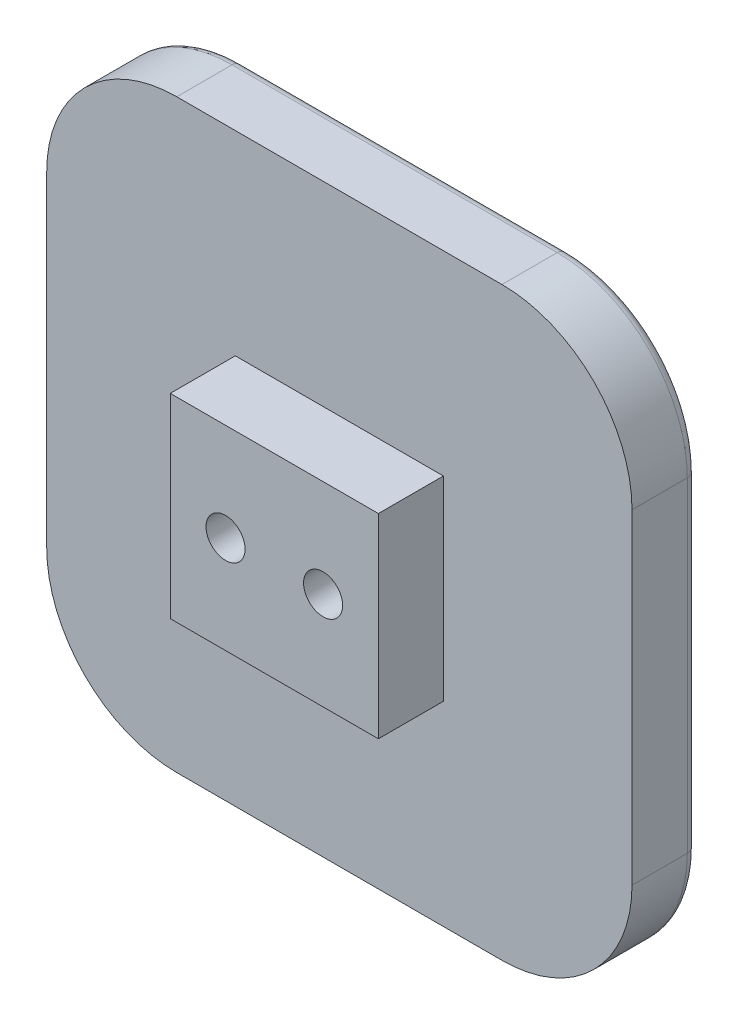
SolidWorks part; units mm, degrees
ref_plane "Ön Düzlem" through (0, 0, 0) normal (0, 0, 1) x (1, 0, 0)
ref_plane "Üst Düzlem" through (0, 0, 0) normal (0, 1, 0) x (1, 0, 0)
ref_plane "Sağ Düzlem" through (0, 0, 0) normal (1, 0, 0) x (0, 0, -1)
sketch "Çizim1" plane through (0, 0, 0) normal (0, 0, 1) x (1, 0, 0)
  line L0 (-41.5414, -1.1109) -> (-41.5414, 48.8891)
  line L1 (-21.5414, 68.8891) -> (28.4586, 68.8891)
  line L2 (-21.5414, -21.1109) -> (28.4586, -21.1109)
  line L3 (48.4586, -1.1109) -> (48.4586, 48.8891)
  arc A0 (-21.5414, 68.8891) -> (-41.5414, 48.8891) centre (-21.5414, 48.8891) ccw
  arc A1 (28.4586, 68.8891) -> (48.4586, 48.8891) centre (28.4586, 48.8891) cw
  arc A2 (28.4586, -21.1109) -> (48.4586, -1.1109) centre (28.4586, -1.1109) ccw
  arc A3 (-21.5414, -21.1109) -> (-41.5414, -1.1109) centre (-21.5414, -1.1109) cw
extrude "Yükseklik-Ekstrüzyon1" add sketch "Çizim1" along normal blind 20
sketch "Sketch1" plane through (0, 0, 0) normal (0, 0, 1) x (1, 0, 0)
  circle A0 centre (-4.0414, 23.8891) radius 2.5
  circle A1 centre (10.9586, 23.8891) radius 2.5
extrude "Cut-Extrude1" cut sketch "Sketch1" along normal blind 44 and the other way blind 10
sketch "Sketch2" plane through (0, 0, 0) normal (0, 0, 1) x (1, 0, 0)
  line L0 (-12.5414, 38.8891) -> (19.4586, 38.8891)
  line L3 (19.4586, 38.8891) -> (19.4586, 68.8891)
  line L4 (28.4586, 68.8891) -> (-21.5414, 68.8891) construction
  line L5 (19.4586, 68.8891) -> (-12.5414, 68.8891)
  line L6 (-12.5414, 68.8891) -> (-12.5414, 38.8891)
extrude "Cut-Extrude3" cut sketch "Sketch2" along normal blind 27
sketch "Sketch3" plane through (0, 0, 0) normal (0, 0, 1) x (1, 0, 0)
  line L1 (-12.5414, 38.8891) -> (19.4586, 38.8891)
  line L2 (-12.5414, 38.8891) -> (-12.5414, 68.8891)
  line L3 (-12.5414, 68.8891) -> (19.4586, 68.8891)
  line L4 (19.4586, 38.8891) -> (19.4586, 68.8891)
extrude "Boss-Extrude1" add sketch "Sketch3" along normal blind 16
sketch "Sketch4" plane through (0, 0, 0) normal (0, 0, 1) x (1, 0, 0)
  line L1 (15.6929, 23.8891) -> (13.3258, 27.9891)
  line L2 (13.3258, 27.9891) -> (8.5915, 27.9891)
  line L3 (8.5915, 27.9891) -> (6.2244, 23.8891)
  line L4 (6.2244, 23.8891) -> (8.5915, 19.7891)
  line L5 (8.5915, 19.7891) -> (13.3258, 19.7891)
  line L6 (13.3258, 19.7891) -> (15.6929, 23.8891)
  line L7 (0.6929, 23.8891) -> (-1.6742, 27.9891)
  line L8 (-1.6742, 27.9891) -> (-6.4085, 27.9891)
  line L9 (-6.4085, 27.9891) -> (-8.7756, 23.8891)
  line L10 (-8.7756, 23.8891) -> (-6.4085, 19.7891)
  line L11 (-6.4085, 19.7891) -> (-1.6742, 19.7891)
  line L12 (-1.6742, 19.7891) -> (0.6929, 23.8891)
  circle A0 centre (10.9586, 23.8891) radius 4.1 construction
  circle A2 centre (-4.0414, 23.8891) radius 4.1 construction
extrude "Cut-Extrude4" cut sketch "Sketch4" along normal blind 4
sketch "Sketch5" plane through (0, 0, 0) normal (0, 0, 1) x (1, 0, 0)
  line L1 (18.9616, 32.8218) -> (-14.5543, 32.8218)
  line L2 (18.9616, 32.8218) -> (18.9616, 14.5135)
  line L3 (18.9616, 14.5135) -> (-14.5543, 14.5135)
  line L4 (-14.5543, 32.8218) -> (-14.5543, 14.5135)
extrude "Boss-Extrude2" add sketch "Sketch5" along normal blind 10
sketch "Sketch6" plane through (0, 0, 0) normal (0, 0, 1) x (1, 0, 0)
  circle A0 centre (-4.0414, 23.8891) radius 2.5
  circle A1 centre (10.9586, 23.8891) radius 2.5
extrude "Cut-Extrude5" cut sketch "Sketch6" against normal blind 25 and the other way blind 53
sketch "Sketch7" plane through (0, 0, 0) normal (0, 0, 1) x (1, 0, 0)
  line L2 (-12.5414, 68.8891) -> (-49.0364, 68.8891)
  line L3 (-12.5414, 68.8891) -> (-12.5414, -22.5963)
  line L4 (-12.5414, -22.5963) -> (-49.0364, -22.5963)
  line L5 (-49.0364, 68.8891) -> (-49.0364, -22.5963)
  line L6 (19.4586, 68.8891) -> (57.7649, 68.8891)
  line L7 (19.4586, 68.8891) -> (19.4586, -22.5963)
  line L8 (19.4586, -22.5963) -> (57.7649, -22.5963)
  line L9 (57.7649, 68.8891) -> (57.7649, -22.5963)
extrude "Cut-Extrude7" cut sketch "Sketch7" along normal blind 30
sketch "Sketch8" plane through (0, 0, 0) normal (0, 0, 1) x (1, 0, 0)
  line L0 (-41.5414, 68.8891) -> (-12.5414, 68.8891)
  line L1 (19.4586, 68.8891) -> (48.4586, 68.8891)
  line L3 (-41.5414, 68.8891) -> (-41.5414, -21.1109)
  line L4 (-41.5414, -21.1109) -> (-12.5414, -21.1109)
  line L5 (-12.5414, 68.8891) -> (-12.5414, -21.1109)
  line L8 (48.4586, 68.8891) -> (48.4586, -21.1109)
  line L9 (48.4586, -21.1109) -> (19.4586, -21.1109)
  line L10 (19.4586, 68.8891) -> (19.4586, -21.1109)
extrude "Boss-Extrude3" add sketch "Sketch8" along normal blind 10
sketch "Sketch9" plane through (0, 0, 0) normal (0, 0, 1) x (1, 0, 0)
  line L0 (-41.5414, 68.8891) -> (-21.5414, 68.8891)
  line L1 (-12.5414, 68.8891) -> (-41.5414, 68.8891) construction
  line L3 (-41.5414, 68.8891) -> (-41.5414, 48.8891)
  line L9 (48.4586, 68.8891) -> (48.4586, 48.8891)
  line L10 (48.4586, 68.8891) -> (28.4586, 68.8891)
  line L11 (48.4586, -21.1109) -> (28.4586, -21.1109)
  line L12 (48.4586, -21.1109) -> (48.4586, -1.1109)
  line L13 (-41.5414, -21.1109) -> (-41.5414, -1.1109)
  line L14 (-41.5414, -21.1109) -> (-21.5414, -21.1109)
  arc A0 (-21.5414, 68.8891) -> (-41.5414, 48.8891) centre (-21.5414, 48.8891) ccw
  arc A1 (28.4586, 68.8891) -> (48.4586, 48.8891) centre (28.4586, 48.8891) cw
  arc A2 (28.4586, -21.1109) -> (48.4586, -1.1109) centre (28.4586, -1.1109) ccw
  arc A3 (-21.5414, -21.1109) -> (-41.5414, -1.1109) centre (-21.5414, -1.1109) cw
extrude "Cut-Extrude8" cut sketch "Sketch9" along normal blind 10
sketch "Sketch10" plane through (0, 0, 0) normal (0, 0, 1) x (1, 0, 0)
  line L0 (19.4586, 38.8891) -> (19.4586, -21.1109) construction
  line L1 (-12.5414, 68.8891) -> (19.4586, 68.8891)
  line L2 (-12.5414, 68.8891) -> (-12.5414, 38.8891)
  line L3 (-12.5414, 38.8891) -> (19.4586, 38.8891)
  line L4 (19.4586, 68.8891) -> (19.4586, 38.8891)
  line L5 (-12.5414, -21.1109) -> (19.4586, -21.1109)
  line L6 (-12.5414, -21.1109) -> (-12.5414, 8.8891)
  line L7 (-12.5414, 8.8891) -> (19.4586, 8.8891)
  line L8 (19.4586, -21.1109) -> (19.4586, 8.8891)
extrude "Cut-Extrude9" cut sketch "Sketch10" along normal blind 28
sketch "Sketch11" plane through (0, 0, 0) normal (0, 0, 1) x (1, 0, 0)
  line L1 (-12.5414, 38.8891) -> (19.4586, 38.8891)
  line L2 (-12.5414, 38.8891) -> (-12.5414, 68.8891)
  line L3 (-12.5414, 68.8891) -> (19.4586, 68.8891)
  line L4 (19.4586, 38.8891) -> (19.4586, 68.8891)
  line L5 (-12.5414, 8.8891) -> (19.4586, 8.8891)
  line L6 (-12.5414, 8.8891) -> (-12.5414, -21.1109)
  line L7 (-12.5414, -21.1109) -> (19.4586, -21.1109)
  line L8 (19.4586, 8.8891) -> (19.4586, -21.1109)
extrude "Boss-Extrude4" add sketch "Sketch11" along normal blind 10
sketch "Sketch12" plane through (0, 0, 0) normal (0, 0, 1) x (1, 0, 0)
  circle A0 centre (-4.0414, 23.8891) radius 3
  circle A1 centre (10.9586, 23.8891) radius 3
extrude "Cut-Extrude10" cut sketch "Sketch12" along normal blind 22
sketch "Sketch13" plane through (0, 0, 0) normal (0, 0, 1) x (1, 0, 0)
  circle A0 centre (10.9586, 23.8891) radius 6
  circle A1 centre (-4.0414, 23.8891) radius 6
extrude "Cut-Extrude11" cut sketch "Sketch13" along normal blind 5
fillet "Fillet1" radius 1.5 8 edges at (42.6008, -15.253, 0) (3.4586, -21.1109, 0) (-35.6835, -15.253, 0) (-41.5414, 23.8891, 0) (-35.6835, 63.0312, 0) (3.4586, 68.8891, 0) (42.6008, 63.0312, 0) (48.4586, 23.8891, 0)
